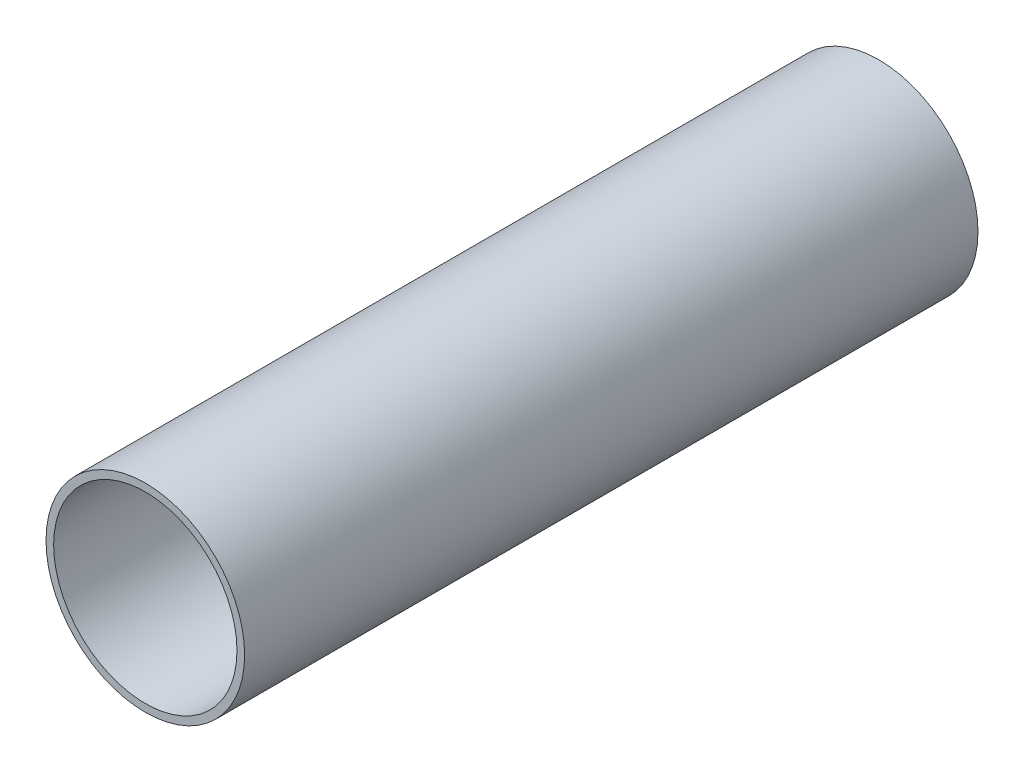
SolidWorks part; units mm, degrees
material "Corrugated Paper"
ref_plane "Front Plane" through (0, 0, 0) normal (0, 0, 1) x (1, 0, 0)
ref_plane "Top Plane" through (0, 0, 0) normal (0, 1, 0) x (1, 0, 0)
ref_plane "Right Plane" through (0, 0, 0) normal (1, 0, 0) x (0, 0, -1)
sketch "Sketch1" plane through (0, 0, 0) normal (0, 0, 1) x (1, 0, 0)
  circle A0 centre (0, 0) radius 38.1
  circle A1 centre (0, 0) radius 41.275
  dimension "D1" = 76.2
  dimension "D2" = 82.55
extrude "Boss-Extrude1" add sketch "Sketch1" along normal blind 304.8
